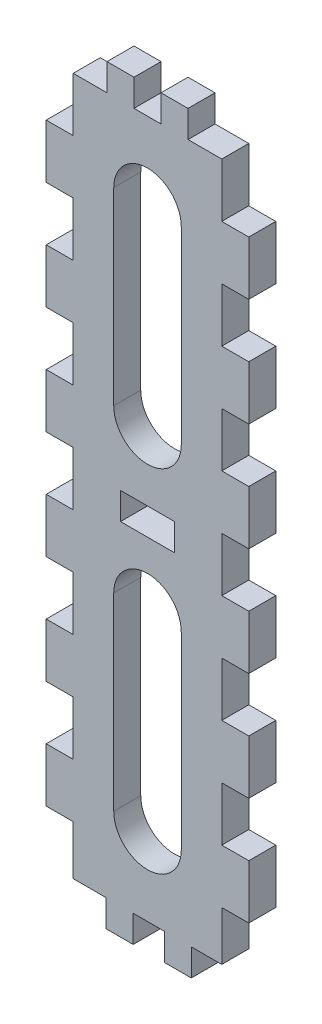
SolidWorks part; units mm, degrees
ref_plane "Front Plane" through (0, 0, 0) normal (0, 0, 1) x (1, 0, 0)
ref_plane "Top Plane" through (0, 0, 0) normal (0, 1, 0) x (1, 0, 0)
ref_plane "Right Plane" through (0, 0, 0) normal (1, 0, 0) x (0, 0, -1)
sketch "Sketch1" plane through (0, 0, 0) normal (0, 0, 1) x (1, 0, 0)
  line L1 (0, -170.3451) -> (-47.625, -170.3451)
  line L2 (0, -170.3451) -> (0, -6.35)
  line L3 (0, -6.35) -> (-47.625, -6.35)
  line L4 (-47.625, -170.3451) -> (-47.625, -6.35)
extrude "Boss-Extrude1" add sketch "Sketch1" against normal blind 6.35 contours L1 L4 L3 L2
sketch "Sketch3" plane through (0, 0, 0) normal (0, 0, 1) x (1, 0, 0)
  line L0 (-30.1625, -6.35) -> (-17.4625, -6.35) construction
  line L1 (0, -6.35) -> (-47.625, -6.35) construction
  line L2 (0, -170.3451) -> (-47.625, -170.3451) construction
  line L3 (-20.6375, -12.7) -> (-14.2875, -12.7)
  line L4 (-20.6375, -12.7) -> (-20.6375, 0)
  line L5 (-20.6375, 0) -> (-14.2875, 0)
  line L6 (-14.2875, -12.7) -> (-14.2875, 0)
  line L7 (-20.6375, -12.7) -> (-14.2875, 0) construction
  line L8 (-20.6375, 0) -> (-14.2875, -12.7) construction
  line L9 (-33.3375, -12.7) -> (-26.9875, -12.7)
  line L10 (-33.3375, -12.7) -> (-33.3375, 0)
  line L11 (-33.3375, 0) -> (-26.9875, 0)
  line L12 (-26.9875, -12.7) -> (-26.9875, 0)
  line L13 (-33.3375, -12.7) -> (-26.9875, 0) construction
  line L14 (-33.3375, 0) -> (-26.9875, -12.7) construction
  line L15 (-27.1764, -163.9951) -> (-33.5264, -163.9951)
  line L16 (-27.1764, -163.9951) -> (-27.1764, -176.6951)
  line L17 (-27.1764, -176.6951) -> (-33.5264, -176.6951)
  line L18 (-33.5264, -163.9951) -> (-33.5264, -176.6951)
  line L19 (-27.1764, -163.9951) -> (-33.5264, -176.6951) construction
  line L20 (-27.1764, -176.6951) -> (-33.5264, -163.9951) construction
  line L22 (-19.8695, -163.9951) -> (-13.5195, -163.9951)
  line L23 (-19.8695, -163.9951) -> (-19.8695, -176.6951)
  line L24 (-19.8695, -176.6951) -> (-13.5195, -176.6951)
  line L25 (-13.5195, -163.9951) -> (-13.5195, -176.6951)
  line L26 (-19.8695, -163.9951) -> (-13.5195, -176.6951) construction
  line L27 (-19.8695, -176.6951) -> (-13.5195, -163.9951) construction
  point P2 (-23.8125, -6.35)
  point P13 (-30.3514, -170.3451)
  point P20 (-16.6945, -170.3451)
  dimension "D1" = 12.7
  dimension "D2" = 6.35
  dimension "D3" = 12.7
extrude "Boss-Extrude2" add sketch "Sketch3" against normal blind 6.35
sketch "Sketch4" plane through (0, 0, 0) normal (0, 0, 1) x (1, 0, 0)
  line L1 (6.35, -6.35) -> (-6.35, -6.35)
  line L2 (6.35, -6.35) -> (6.35, -19.05)
  line L3 (6.35, -19.05) -> (-6.35, -19.05)
  line L4 (-6.35, -6.35) -> (-6.35, -19.05)
  line L5 (-53.975, -6.35) -> (-41.275, -6.35)
  line L6 (-53.975, -6.35) -> (-53.975, -19.05)
  line L7 (-53.975, -19.05) -> (-41.275, -19.05)
  line L8 (-41.275, -6.35) -> (-41.275, -19.05)
  dimension "D1" = 12.7
  dimension "D2" = 12.7
extrude "Cut-Extrude1" cut sketch "Sketch4" against normal through all
pattern_linear "LPattern1" count 7 spacing 25.4 along (0, -1, 0) of "Cut-Extrude1"
sketch "Sketch5" plane through (0, 0, 0) normal (0, 0, 1) x (1, 0, 0)
  line L0 (-6.35, -6.35) -> (-41.275, -170.3451) construction
  line L1 (-23.8125, -129.6225) -> (-23.8125, -47.0725) construction
  line L2 (-23.8125, -107.3975) -> (-23.8125, -151.8475) construction
  line L3 (-15.875, -107.3975) -> (-15.875, -151.8475)
  line L4 (-31.75, -107.3975) -> (-31.75, -151.8475)
  line L5 (-23.8125, -69.2975) -> (-23.8125, -24.8475) construction
  line L6 (-31.75, -69.2975) -> (-31.75, -24.8475)
  line L7 (-15.875, -69.2975) -> (-15.875, -24.8475)
  arc A0 (-15.875, -107.3975) -> (-31.75, -107.3975) centre (-23.8125, -107.3975) ccw
  arc A1 (-31.75, -151.8475) -> (-15.875, -151.8475) centre (-23.8125, -151.8475) ccw
  arc A2 (-31.75, -69.2975) -> (-15.875, -69.2975) centre (-23.8125, -69.2975) ccw
  arc A3 (-15.875, -24.8475) -> (-31.75, -24.8475) centre (-23.8125, -24.8475) ccw
  point P6 (-23.8125, -88.3475)
  point P9 (-23.8125, -129.6225)
  point P16 (-23.8125, -47.0725)
  dimension "D2" = 44.45
  dimension "D3" = 7.9375
  dimension "D1" = 82.55
extrude "Weight savings" cut sketch "Sketch5" against normal through all
sketch "Sketch6" plane through (0, 0, -6.35) normal (0, 0, -1) x (-1, 0, 0)
  line L0 (6.35, -95.25) -> (41.275, -82.55) construction
  line L2 (30.1625, -92.075) -> (17.4625, -92.075)
  line L3 (30.1625, -92.075) -> (30.1625, -85.725)
  line L4 (30.1625, -85.725) -> (17.4625, -85.725)
  line L5 (17.4625, -92.075) -> (17.4625, -85.725)
  line L6 (30.1625, -92.075) -> (17.4625, -85.725) construction
  line L7 (30.1625, -85.725) -> (17.4625, -92.075) construction
  point P4 (23.8125, -88.9)
  dimension "D1" = 6.35
  dimension "D2" = 12.7
extrude "Center Panel Mate" cut sketch "Sketch6" against normal through all
